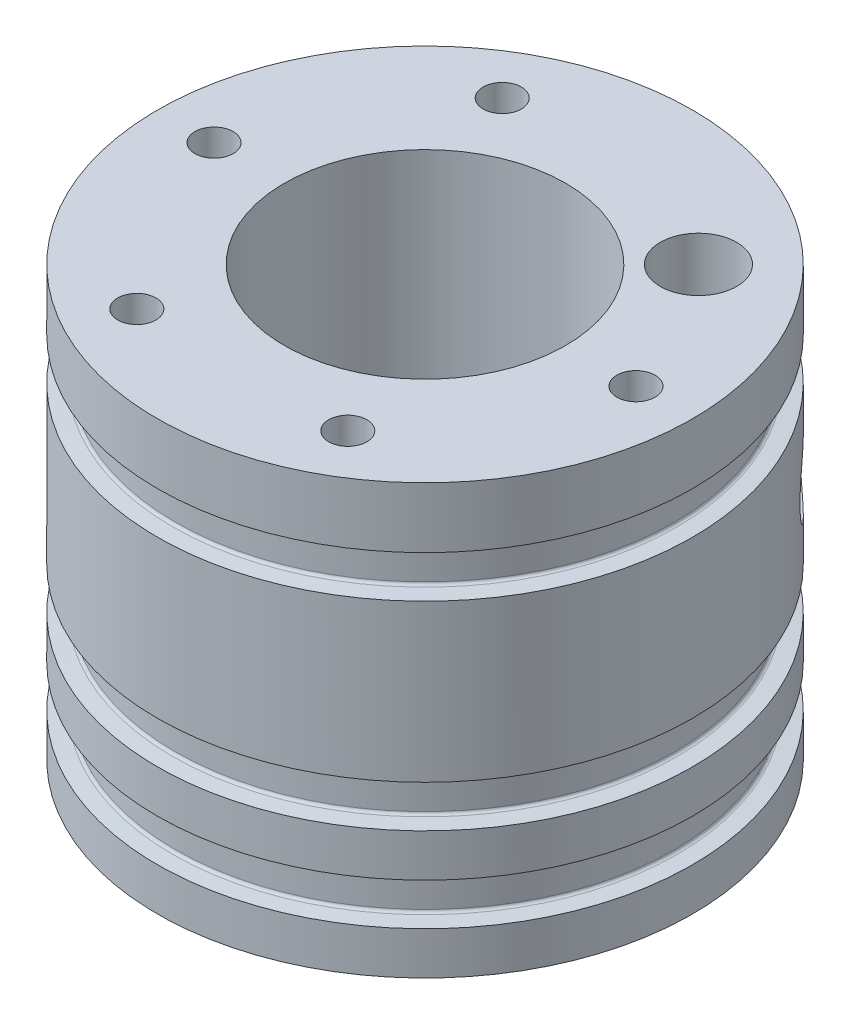
SolidWorks part; units mm, degrees
ref_plane "Front Plane" through (0, 0, 0) normal (0, 0, 1) x (1, 0, 0)
ref_plane "Top Plane" through (0, 0, 0) normal (0, 1, 0) x (1, 0, 0)
ref_plane "Right Plane" through (0, 0, 0) normal (1, 0, 0) x (0, 0, -1)
sketch "Sketch1" plane through (0, 0, 0) normal (0, 0, 1) x (1, 0, 0)
  line L0 (0, 0) -> (0, 54.9837) construction
  line L1 (6.8961, 0) -> (6.8961, 3.81)
  line L2 (6.8961, 3.81) -> (12.7, 12.0988)
  line L3 (12.7, 12.0988) -> (12.7, 38.735)
  line L4 (6.8961, 0) -> (24.1554, 0)
  line L13 (24.1554, 0) -> (24.1554, 38.735)
  line L14 (24.1554, 38.735) -> (12.7, 38.735)
  line L15 (24.1554, 3.81) -> (6.8961, 3.81) construction
  point P8 (24.1554, 3.81)
  point P9 (24.1554, 7.62)
  dimension "D1" = 13.7922
  dimension "D2" = 48.3108
  dimension "D3" = 25.4
  dimension "D4" = 35
  dimension "D5" = 3.81
  dimension "D6" = 38.735
  dimension "D7" = 3.81
revolve "Revolve1" add sketch "Sketch1" angle 360 about L0
ref_plane "Plane1" through (0, 38.735, 0) normal (-1, 0, 0) x (0, 0, 1)
sketch "Sketch2" plane through (0, 38.735, 0) normal (-1, 0, 0) x (0, 0, 1)
  line L0 (14.9352, -1.0889) -> (14.8399, 0)
  line L1 (14.8399, 0) -> (17.6721, 0)
  line L2 (17.6721, 0) -> (17.5768, -1.0889)
  line L3 (17.3238, -1.3208) -> (15.1882, -1.3208)
  line L4 (0, 50) -> (0, -50) construction
  arc A0 (17.5768, -1.0889) -> (17.3238, -1.3208) centre (17.3238, -1.0668) cw
  arc A1 (15.1882, -1.3208) -> (14.9352, -1.0889) centre (15.1882, -1.0668) cw
revolve "Groove for AS 568-025, O-Ring1" cut sketch "Sketch2"
ref_plane "Plane2" through (0, 0, 0) normal (-1, 0, 0) x (0, 0, -1)
ref_plane "Plane3" through (0, 0, 0) normal (-1, 0, 0) x (0, 0, -1)
sketch "Sketch6" plane through (0, 0, 0) normal (-1, 0, 0) x (0, 0, -1)
  line L0 (22.7744, -3.9775) -> (24.6888, -3.81)
  line L1 (24.6888, -3.81) -> (24.6888, -7.701)
  line L2 (24.6888, -7.701) -> (22.7744, -7.5335)
  line L3 (22.5425, -7.2805) -> (22.5425, -4.2305)
  line L4 (0, 50) -> (0, -50) construction
  line L5 (0, 0) -> (0, -54.9837) construction
  line L6 (24.1554, 0) -> (-24.1554, 0) construction
  arc A0 (22.7744, -7.5335) -> (22.5425, -7.2805) centre (22.7965, -7.2805) cw
  arc A1 (22.5425, -4.2305) -> (22.7744, -3.9775) centre (22.7965, -4.2305) cw
  dimension "D1" = 3.81
revolve "Groove for AS 568-132, O-Ring2" cut sketch "Sketch6" angle 360 about L4
sketch "Sketch4" plane through (0, 0, 0) normal (-1, 0, 0) x (0, 0, -1)
  line L0 (22.7744, -11.6318) -> (24.6888, -11.4643)
  line L1 (24.6888, -11.4643) -> (24.6888, -15.3553)
  line L2 (24.6888, -15.3553) -> (22.7744, -15.1878)
  line L3 (22.5425, -14.9348) -> (22.5425, -11.8848)
  line L4 (0, 50) -> (0, -50) construction
  line L5 (0, 0) -> (0, -54.9837) construction
  line L7 (-24.1554, -7.6543) -> (24.1554, -7.6543) construction
  arc A0 (22.7744, -15.1878) -> (22.5425, -14.9348) centre (22.7965, -14.9348) cw
  arc A1 (22.5425, -11.8848) -> (22.7744, -11.6318) centre (22.7965, -11.8848) cw
  dimension "D1" = 3.81
revolve "Groove for AS 568-132, O-Ring1" cut sketch "Sketch4" angle 360 about L4
hole_wizard "#8-32 Tapped Hole1" positions "Sketch7" profile "Sketch9" tap size "#8-32" standard "ANSI Inch"
sketch "Sketch7" plane through (0, 38.735, 0) normal (0, 1, 0) x (1, 0, 0)
  line L0 (19.05, 0) -> (0, 0) construction
  circle A0 centre (0, 0) radius 19.05 construction
  point P9 (19.05, 0)
  dimension "D1" = 38.1
sketch "Sketch9" plane through (19.05, 38.735, 0) normal (1, 0, 0) x (0, 0, 1)
  line L0 (0, 0) -> (0, 10.5628)
  line L1 (0, 10.5628) -> (1.7272, 9.525)
  line L2 (1.7272, 9.525) -> (1.7272, 0)
  line L5 (1.7272, 0) -> (0, 0)
  line L10 (0, 10.5628) -> (-1.7272, 9.525) construction
  line L11 (0, -6.35) -> (0, 107.95) construction
  dimension "Tap Drill Dia." = 3.4544
  dimension "Tap Drill Depth" = 9.525
  dimension "Drill Angle" = 118
cosmetic thread "Hole Thread1" parameters "D1"=9.525, "D2"=4.1656
pattern_circular "CirPattern1" count 6 over 360 about axis through (0, 0, 0) along (0, 1, 0) skipping 5 of "#8-32 Tapped Hole1"
cosmetic thread "Hole Thread2" parameters "D1"=9.525, "D2"=4.1656
cosmetic thread "Hole Thread3" parameters "D1"=9.525, "D2"=4.1656
cosmetic thread "Hole Thread4" parameters "D1"=9.525, "D2"=4.1656
cosmetic thread "Hole Thread5" parameters "D1"=9.525, "D2"=4.1656
ref_plane "Plane4" through (0, 0, 0) normal (-1, 0, 0) x (0, 0, -1)
sketch "Sketch11" plane through (0, 0, 0) normal (-1, 0, 0) x (0, 0, -1)
  line L0 (22.7744, -29.5922) -> (24.6888, -29.4247)
  line L1 (24.6888, -29.4247) -> (24.6888, -33.3156)
  line L2 (24.6888, -33.3156) -> (22.7744, -33.1482)
  line L3 (22.5425, -32.8951) -> (22.5425, -29.8452)
  line L4 (0, 50) -> (0, -50) construction
  arc A0 (22.7744, -33.1482) -> (22.5425, -32.8951) centre (22.7965, -32.8951) cw
  arc A1 (22.5425, -29.8452) -> (22.7744, -29.5922) centre (22.7965, -29.8452) cw
revolve "Groove for AS 568-132, O-Ring3" cut sketch "Sketch11" angle 360 about L4
ref_plane "Plane5" through (17.0804, 0, -17.0804) normal (0.7071, 0, -0.7071) x (0, -1, 0)
sketch "Sketch15" plane through (17.0804, 0, -17.0804) normal (0.7071, 0, -0.7071) x (0, -1, 0)
  line L3 (0, 0) -> (-22.225, 0) construction
  circle A2 centre (-22.225, 0) radius 3.175
  point P1 (0, 0)
  point P2 (0, 0)
  point P5 (0, 0)
  dimension "D1" = 6.35
  dimension "D2" = 22.225
extrude "Cut-Extrude1" cut sketch "Sketch15" against normal up to surface (11.8587 mm away)
hole_wizard "5/16-24 Tapped Hole1" positions "Sketch12" profile "Sketch14" tap size "5/16-24" standard "ANSI Inch"
sketch "Sketch12" plane through (0, 38.735, 0) normal (0, 1, 0) x (1, 0, 0)
  line L0 (0, 0) -> (20.621, 0) construction
  line L2 (0, 0) -> (12.3479, 12.3479) construction
  circle A0 centre (0, 0) radius 17.4625 construction
  point P0 (12.3479, 12.3479)
  dimension "D1" = 34.925
  dimension "D2" = 45
cosmetic thread "Hole Thread6" parameters "D1"=10.16, "D2"=7.9375
sketch "Sketch14" plane through (12.3479, 38.735, -12.3479) normal (1, 0, 0) x (0, 0, 1)
  line L0 (0, 0) -> (0, 18.5846)
  line L1 (0, 18.5846) -> (3.4544, 16.509)
  line L2 (3.4544, 16.509) -> (3.4544, 0)
  line L5 (3.4544, 0) -> (0, 0)
  line L10 (0, 18.5846) -> (-3.4544, 16.509) construction
  line L11 (0, -6.35) -> (0, 107.95) construction
  dimension "Tap Drill Dia." = 6.9088
  dimension "Tap Drill Depth" = 16.509
  dimension "Drill Angle" = 118
